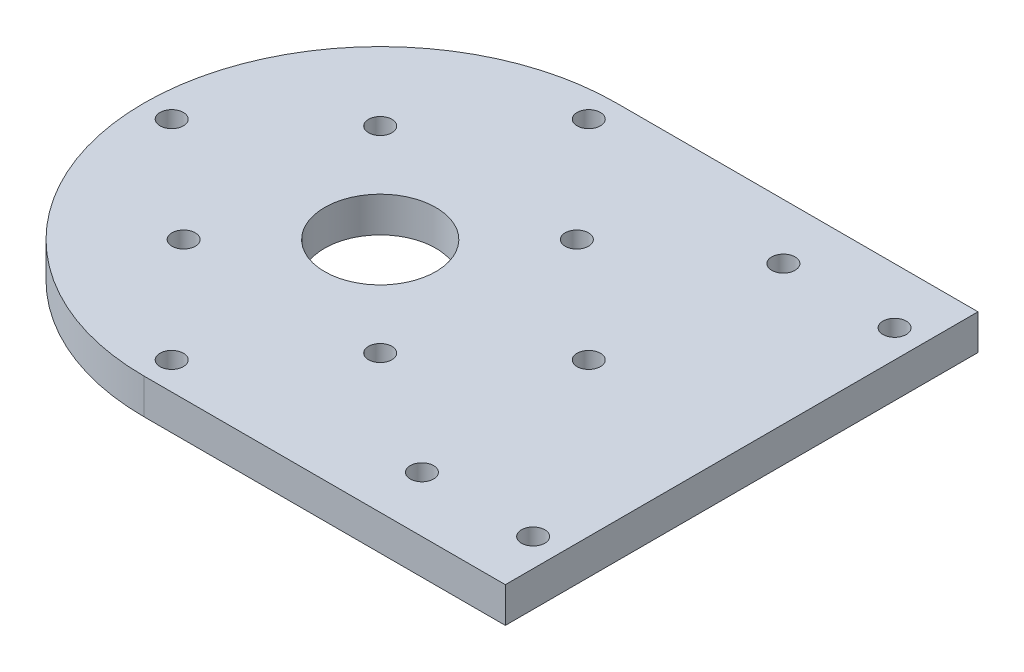
SolidWorks part; units mm, degrees
ref_plane "Front Plane" through (0, 0, 0) normal (0, 0, 1) x (1, 0, 0)
ref_plane "Top Plane" through (0, 0, 0) normal (0, 1, 0) x (1, 0, 0)
ref_plane "Right Plane" through (0, 0, 0) normal (1, 0, 0) x (0, 0, -1)
sketch "Sketch1" plane through (0, 0, 0) normal (0, 1, 0) x (1, 0, 0)
  line L0 (0, 0) -> (65, 0) construction
  line L1 (0, 42.5) -> (65, 42.5)
  line L6 (0, -42.5) -> (65, -42.5)
  line L7 (65, 42.5) -> (65, -42.5)
  line L10 (65, 32.5) -> (40, 32.5) construction
  line L13 (40, 32.5) -> (40, -32.5) construction
  line L16 (40, -32.5) -> (65, -32.5) construction
  line L19 (-17.6777, 17.6777) -> (17.6777, -17.6777) construction
  line L20 (60, 32.5) -> (60, -32.5) construction
  line L24 (17.6777, 17.6777) -> (-17.6777, -17.6777) construction
  circle A1 centre (0, 0) radius 10
  circle A4 centre (0, 0) radius 14.2875 construction
  circle A8 centre (0, 0) radius 37.5 construction
  circle A13 centre (0, 0) radius 42.5
  circle A28 centre (0, 0) radius 27.94 construction
  circle A38 centre (-37.5, 0) radius 2.1
  circle A39 centre (0, 37.5) radius 2.1
  circle A40 centre (0, -37.5) radius 2.1
  circle A41 centre (37.5, 0) radius 2.1
  circle A42 centre (40, 32.5) radius 2.1
  circle A43 centre (60, 32.5) radius 2.1
  circle A44 centre (40, -32.5) radius 2.1
  circle A45 centre (60, -32.5) radius 2.1
  circle A47 centre (0, 0) radius 25 construction
  circle A48 centre (-17.6777, -17.6777) radius 2.1
  circle A49 centre (-17.6777, 17.6777) radius 2.1
  circle A50 centre (17.6777, 17.6777) radius 2.1
  circle A51 centre (17.6777, -17.6777) radius 2.1
  dimension "D2" = 20
  dimension "D4" = 5
  dimension "D5" = 50
  dimension "D6" = 28.575
  dimension "D7" = 4.2
  dimension "D9" = 55.88
  dimension "D10" = 85
  dimension "D8" = 75
  dimension "D11" = 4.2
  dimension "D12" = 45
  dimension "D13" = 4.2
  dimension "D16" = 20
  dimension "D20" = 10
  dimension "D3" = 65
  dimension "D21" = 10
extrude "Boss-Extrude1" add sketch "Sketch1" against normal blind 6.35
